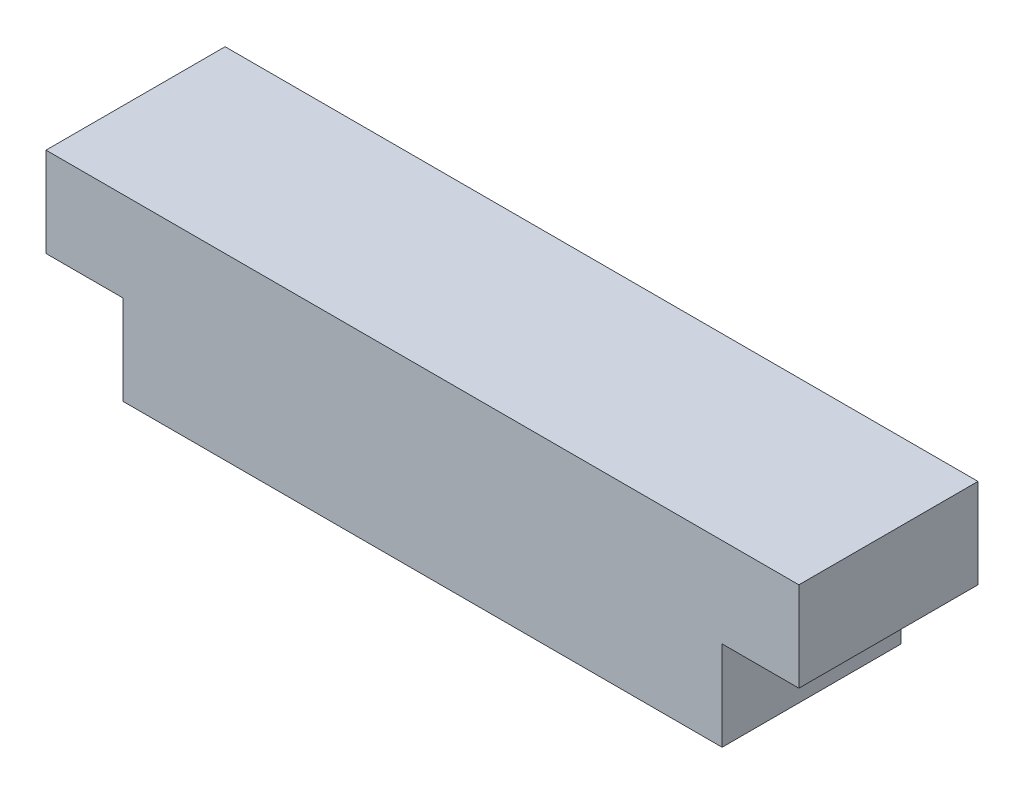
SolidWorks part; units mm, degrees
ref_plane "Front Plane" through (0, 0, 0) normal (0, 0, 1) x (1, 0, 0)
ref_plane "Top Plane" through (0, 0, 0) normal (0, 1, 0) x (1, 0, 0)
ref_plane "Right Plane" through (0, 0, 0) normal (1, 0, 0) x (0, 0, -1)
sketch "Sketch1" plane through (0, 0, 0) normal (0, 0, 1) x (1, 0, 0)
  line L1 (-21.25, -3.175) -> (21.25, -3.175)
  line L2 (-21.25, -3.175) -> (-21.25, 3.175)
  line L3 (-21.25, 3.175) -> (21.25, 3.175)
  line L4 (21.25, -3.175) -> (21.25, 3.175)
  line L5 (-21.25, -3.175) -> (21.25, 3.175) construction
  line L6 (-21.25, 3.175) -> (21.25, -3.175) construction
  point P0 (0, 0)
  dimension "D1" = 42.5
  dimension "D2" = 6.35
extrude "Boss-Extrude1" add sketch "Sketch1" along normal blind 12.7
sketch "Sketch2" plane through (0, 0, 12.7) normal (0, 0, 1) x (1, 0, 0)
  line L0 (21.25, 3.175) -> (-21.25, 3.175) construction
  line L1 (-26.6937, 3.175) -> (26.6938, 3.175)
  line L2 (-26.6937, 3.175) -> (-26.6937, 9.525)
  line L3 (-26.6937, 9.525) -> (26.6938, 9.525)
  line L4 (26.6938, 3.175) -> (26.6938, 9.525)
  line L5 (-26.6937, 3.175) -> (26.6938, 9.525) construction
  line L6 (-26.6937, 9.525) -> (26.6938, 3.175) construction
  point P4 (0, 6.35)
  point P7 (0, 0)
  dimension "D1" = 53.3875
  dimension "D2" = 6.35
extrude "Boss-Extrude2" add sketch "Sketch2" against normal up to surface (12.7 mm away) up to face at (0, 0, 0)
